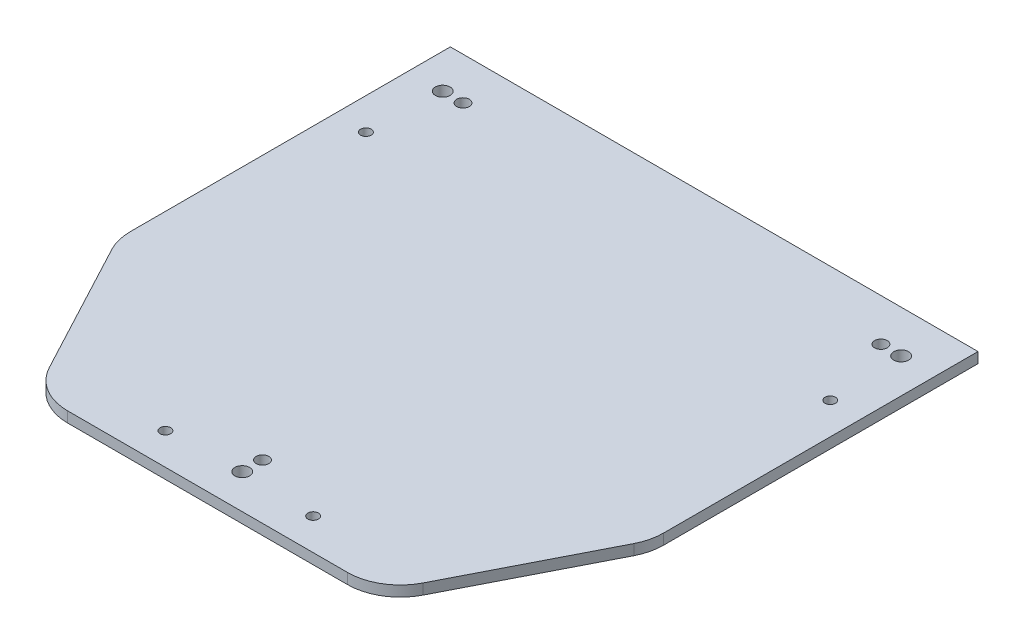
SolidWorks part; units mm, degrees
ref_plane "Plano frontal" through (0, 0, 0) normal (0, 0, 1) x (1, 0, 0)
ref_plane "Plano superior" through (0, 0, 0) normal (0, 1, 0) x (1, 0, 0)
ref_plane "Plano direito" through (0, 0, 0) normal (1, 0, 0) x (0, 0, -1)
sketch "Esboço1" plane through (0, 0, 0) normal (0, 1, 0) x (1, 0, 0)
  line L0 (602.5273, -115.797) -> (470.0074, -115.797)
  line L2 (411.2674, 124.203) -> (661.2674, 124.203)
  line L3 (661.2674, 84.203) -> (661.2674, -24.7556)
  line L4 (411.2674, 81.5882) -> (411.2674, -27.3704)
  line L5 (661.2674, 124.203) -> (661.2674, 84.203)
  line L12 (624.7901, -102.1709) -> (658.5302, -36.1295)
  line L14 (411.2674, 124.203) -> (411.2674, 81.5882)
  line L16 (447.936, -102.538) -> (414.1959, -39.1114)
  arc A0 (414.1959, -39.1114) -> (411.2674, -27.3704) centre (436.2674, -27.3704) cw
  arc A1 (447.936, -102.538) -> (470.0074, -115.797) centre (470.0074, -90.797) ccw
  arc A2 (624.7901, -102.1709) -> (602.5273, -115.797) centre (602.5273, -90.797) cw
  arc A3 (658.5302, -36.1295) -> (661.2674, -24.7556) centre (636.2674, -24.7556) ccw
  dimension "D3" = 240
  dimension "D1" = 25
  dimension "D2" = 250
extrude "Ressalto-extrusão4" add sketch "Esboço1" along normal blind 5
sketch "Esboço2" plane through (0, 5, 0) normal (0, 1, 0) x (1, 0, 0)
  line L0 (411.2674, 124.203) -> (661.2674, 124.203) construction
  line L1 (536.2674, -115.797) -> (536.2674, -99.397) construction
  line L2 (426.2674, 69.0882) -> (426.2674, 69.203) construction
  line L3 (426.2674, 69.203) -> (411.2674, 69.203) construction
  line L4 (602.5273, -115.797) -> (470.0074, -115.797) construction
  line L5 (536.2674, -115.797) -> (536.2674, -89.797) construction
  line L6 (571.2674, -115.797) -> (571.2674, -100.797) construction
  line L7 (571.2674, -100.797) -> (568.7674, -100.797) construction
  line L8 (661.2674, 124.203) -> (661.2674, 104.203) construction
  line L9 (661.2674, 124.203) -> (661.2674, -24.7556) construction
  line L10 (503.7674, -100.797) -> (501.2674, -100.797) construction
  line L11 (501.2674, -100.797) -> (501.2674, -115.797) construction
  line L12 (661.2674, 104.203) -> (644.8674, 104.203) construction
  line L13 (661.2674, 69.203) -> (646.2674, 69.203) construction
  line L14 (661.2674, 104.203) -> (635.2674, 104.203) construction
  line L15 (411.2674, 124.203) -> (411.2674, 104.203) construction
  line L17 (411.2674, 124.203) -> (411.2674, -27.3704) construction
  line L18 (411.2674, 104.203) -> (427.6674, 104.203) construction
  line L19 (411.2674, 104.203) -> (437.2674, 104.203) construction
  circle A0 centre (571.2674, -100.797) radius 2.5
  circle A1 centre (501.2674, -100.797) radius 2.5
  circle A2 centre (646.2674, 69.203) radius 2.5
  circle A4 centre (426.2674, 69.203) radius 2.5
  circle A5 centre (536.2674, -99.397) radius 3.5
  circle A6 centre (536.2674, -89.797) radius 3
  circle A7 centre (644.8674, 104.203) radius 3.5
  circle A8 centre (635.2674, 104.203) radius 3
  circle A9 centre (427.6674, 104.203) radius 3.5
  circle A10 centre (437.2674, 104.203) radius 3
  dimension "D1" = 15
  dimension "D2" = 55
  dimension "D3" = 55
  dimension "D4" = 15
  dimension "D5" = 15
  dimension "D8" = 15
  dimension "D9" = 70
extrude "Corte-extrusão1" cut sketch "Esboço2" against normal blind 5
